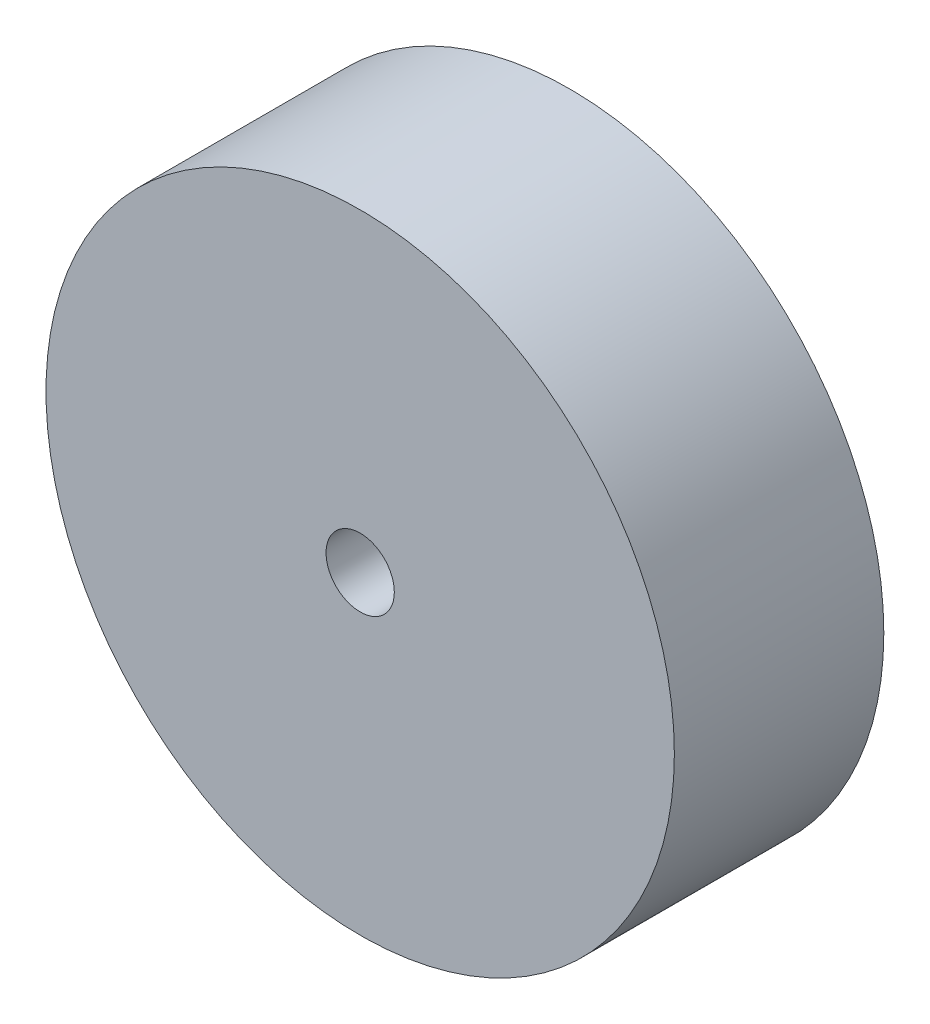
SolidWorks part; units mm, degrees
ref_plane "Front Plane" through (0, 0, 0) normal (0, 0, 1) x (1, 0, 0)
ref_plane "Top Plane" through (0, 0, 0) normal (0, 1, 0) x (1, 0, 0)
ref_plane "Right Plane" through (0, 0, 0) normal (1, 0, 0) x (0, 0, -1)
sketch "Sketch1" plane through (0, 0, 0) normal (0, 0, 1) x (1, 0, 0)
  circle A0 centre (0, 0) radius 7.5
  circle A1 centre (0, 0) radius 0.815
  dimension "D1" = 1.63
  dimension "D2" = 15
extrude "Boss-Extrude1" add sketch "Sketch1" along normal blind 5
